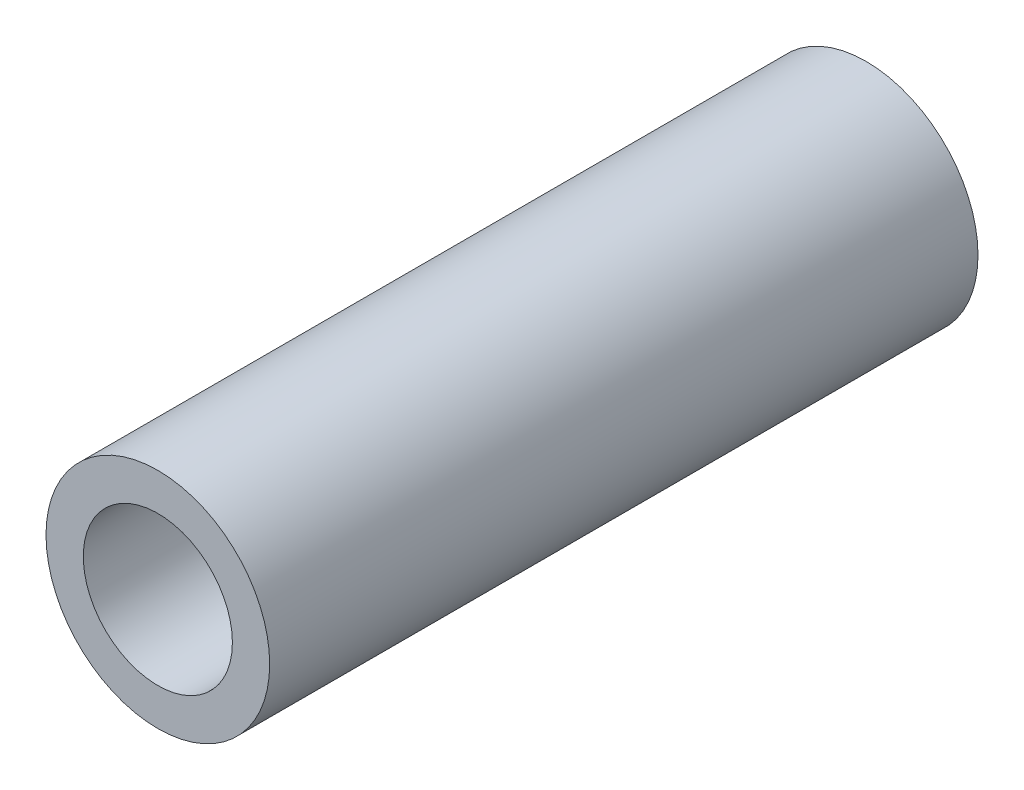
SolidWorks part; units mm, degrees
ref_plane "Front Plane" through (0, 0, 0) normal (0, 0, 1) x (1, 0, 0)
ref_plane "Top Plane" through (0, 0, 0) normal (0, 1, 0) x (1, 0, 0)
ref_plane "Right Plane" through (0, 0, 0) normal (1, 0, 0) x (0, 0, -1)
sketch "Sketch1" plane through (0, 0, 0) normal (0, 0, 1) x (1, 0, 0)
  circle A0 centre (0, 0) radius 2
  circle A1 centre (0, 0) radius 3
  dimension "D1" = 4
  dimension "D2" = 6
extrude "Boss-Extrude1" add sketch "Sketch1" along normal blind 19
